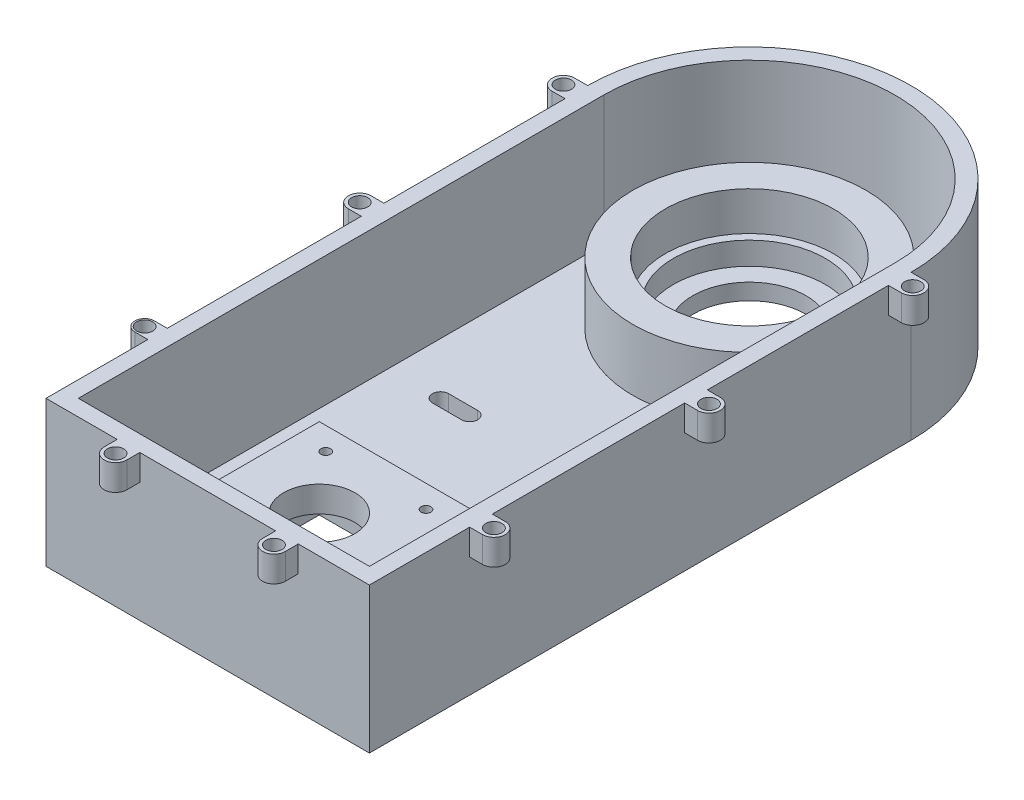
SolidWorks part; units mm, degrees
ref_plane "Front Plane" through (0, 0, 0) normal (0, 0, 1) x (1, 0, 0)
ref_plane "Top Plane" through (0, 0, 0) normal (0, 1, 0) x (1, 0, 0)
ref_plane "Right Plane" through (0, 0, 0) normal (1, 0, 0) x (0, 0, -1)
sketch "Sketch1" plane through (0, 0, 0) normal (0, 1, 0) x (1, 0, 0)
  line L0 (0, 0) -> (45, 0)
  line L1 (0, 0) -> (-45, 0)
  line L2 (0, 0) -> (0, -132.5)
  line L3 (0, -132.5) -> (0, -162.5)
  line L4 (-45, 0) -> (-45, -162.5)
  line L5 (0, -162.5) -> (45, -162.5)
  line L6 (45, 0) -> (45, -162.5)
  line L7 (0, -162.5) -> (-45, -162.5)
  line L8 (50, 0) -> (50, -167.5)
  line L9 (50, -167.5) -> (-50, -167.5)
  line L10 (-50, -167.5) -> (-50, 0)
  circle A0 centre (0, 0) radius 36
  arc A1 (-45, 0) -> (45, 0) centre (0, 0) cw
  arc A2 (-50, 0) -> (50, 0) centre (0, 0) cw
extrude "Boss-Extrude1" add sketch "Sketch1" along normal blind 5 contours L10 A2 L8 L9
sketch "Sketch2" plane through (0, 5, 0) normal (0, 1, 0) x (1, 0, 0)
  line L1 (-50, -167.5) -> (-50, 0) construction
  line L3 (-50, 0) -> (-45, 0)
  line L4 (-45, 0) -> (-45, -162.5)
  line L5 (-45, -162.5) -> (45, -162.5)
  line L6 (45, -162.5) -> (45, 0)
  arc A0 (-45, 0) -> (45, 0) centre (0, 0) cw
extrude "Boss-Extrude2" add sketch "Sketch2" along normal blind 40
sketch "Sketch3" plane through (0, 5, 0) normal (0, 1, 0) x (1, 0, 0)
  circle A0 centre (0, 0) radius 17.5
extrude "Cut-Extrude1" cut sketch "Sketch3" against normal blind 40
sketch "Sketch4" plane through (0, 5, 0) normal (0, 1, 0) x (1, 0, 0)
  circle A0 centre (0, 0) radius 23.5
  circle A1 centre (0, 0) radius 26
extrude "Boss-Extrude3" add sketch "Sketch4" along normal blind 7 contours A1 A0
sketch "Sketch5" plane through (0, 5, 0) normal (0, 1, 0) x (1, 0, 0)
  circle A0 centre (0, 0) radius 36
  circle M1 centre (0, 0) radius 26
extrude "Boss-Extrude4" add sketch "Sketch5" along normal blind 19 contours A0 M1
sketch "Sketch6" plane through (0, 5, 0) normal (0, 1, 0) x (1, 0, 0)
  line L2 (24.5, -133) -> (24.5, -157.5)
  line L3 (24.5, -157.5) -> (-24.5, -157.5)
  line L4 (-24.5, -157.5) -> (-24.5, -108.5)
  line L5 (-24.5, -108.5) -> (24.5, -108.5)
  line L6 (24.5, -108.5) -> (24.5, -133)
extrude "Boss-Extrude5" add sketch "Sketch6" along normal blind 17
sketch "Sketch7" plane through (0, 0, 0) normal (0, -1, 0) x (1, 0, 0)
  line L2 (21.5, 133) -> (21.5, 154.5)
  line L3 (21.5, 154.5) -> (-21.5, 154.5)
  line L4 (-21.5, 154.5) -> (-21.5, 111.5)
  line L5 (-21.5, 111.5) -> (21.5, 111.5)
  line L6 (21.5, 111.5) -> (21.5, 133)
extrude "Cut-Extrude2" cut sketch "Sketch7" against normal blind 14
sketch "Sketch8" plane through (0, 14, 0) normal (0, -1, 0) x (1, 0, 0)
  circle A1 centre (-15.5, 148.5) radius 1.5
  circle A2 centre (15.5, 148.5) radius 1.5
  circle A3 centre (-15.5, 115.5) radius 1.5
  circle A4 centre (15.5, 115.5) radius 1.5
  circle A5 centre (0, 133) radius 11
extrude "Cut-Extrude3" cut sketch "Sketch8" against normal blind 14
sketch "Sketch9" plane through (0, 45, 0) normal (0, 1, 0) x (1, 0, 0)
  line L0 (50, 0) -> (54, 0)
  line L1 (0, 0) -> (0, -133)
  line L2 (54, -7) -> (50, -7)
  line L5 (50, -167.5) -> (50, 0) construction
  line L10 (-20, -64) -> (-29, -64)
  line L11 (-20, -69) -> (-29, -69)
  line L12 (20, -64) -> (29, -64)
  line L13 (20, -69) -> (29, -69)
  arc A0 (54, 0) -> (54, -7) centre (54, -3.5) cw
  circle A1 centre (54, -3.5) radius 2.5
  circle A2 centre (0, -133) radius 2.5
  circle A5 centre (-20, -66.5) radius 2.5
  circle A6 centre (20, -66.5) radius 2.5
  arc A7 (-29, -64) -> (-29, -69) centre (-29, -66.5) ccw
  arc A9 (29, -64) -> (29, -69) centre (29, -66.5) cw
extrude "Cut-Extrude4" cut sketch "Sketch9" against normal blind 45 contours L10 A7 L11 A5 | A5 | A9 L12 A6 L13 | A6
sketch "Sketch10" plane through (0, 45, 0) normal (0, 1, 0) x (1, 0, 0)
  line L0 (50, 0) -> (54, 0)
  line L1 (20, -64) -> (20, -69)
  line L2 (54, -7) -> (50, -7)
  line L3 (50, -63) -> (54, -63)
  line L4 (50, -167.5) -> (50, 0) construction
  line L5 (50, -70) -> (54, -70)
  line L7 (50, -129.5) -> (54, -129.5)
  line L8 (50, -136.5) -> (54, -136.5)
  line L9 (-50, 0) -> (-54, 0)
  line L10 (-50, -7) -> (-54, -7)
  line L11 (-50, 0) -> (-50, -167.5) construction
  line L13 (-50, -63) -> (-54, -63)
  line L14 (-50, -70) -> (-54, -70)
  line L15 (-50, -130) -> (-54, -130)
  line L16 (-50, -136) -> (-54, -136)
  line L18 (21, -167.5) -> (21, -171.5)
  line L19 (-50, -167.5) -> (50, -167.5) construction
  line L20 (28, -167.5) -> (28, -171.5)
  line L21 (-21, -167.5) -> (-21, -171.5)
  line L22 (-28, -167.5) -> (-28, -171.5)
  arc A0 (54, 0) -> (54, -7) centre (54, -3.5) cw
  circle A1 centre (54, -3.5) radius 2.5
  arc A2 (20, -64) -> (20, -69) centre (20, -66.5) ccw construction
  circle A3 centre (54, -66.5) radius 2.5
  arc A4 (54, -63) -> (54, -70) centre (54, -66.5) cw
  circle A5 centre (54, -133) radius 2.5
  arc A6 (54, -129.5) -> (54, -136.5) centre (54, -133) cw
  circle A7 centre (-54, -3.5) radius 2.5
  arc A8 (-54, 0) -> (-54, -7) centre (-54, -3.5) ccw
  circle A9 centre (-54, -66.5) radius 2.5
  arc A10 (-54, -63) -> (-54, -70) centre (-54, -66.5) ccw
  circle A11 centre (-54, -133) radius 2.5
  arc A12 (-54, -130) -> (-54, -136) centre (-54, -133) ccw
  circle A13 centre (-24.5, -171.5) radius 2.5
  circle A14 centre (24.5, -171.5) radius 2.5
  arc A15 (-28, -171.5) -> (-21, -171.5) centre (-24.5, -171.5) ccw
  arc A16 (21, -171.5) -> (28, -171.5) centre (24.5, -171.5) ccw
  line M6 (-50, 0) -> (-50, -167.5)
  line M7 (-50, -167.5) -> (50, -167.5)
  line M8 (50, -167.5) -> (50, 0)
extrude "Boss-Extrude6" add sketch "Sketch10" against normal blind 8 contours L13 A10 L14 A9 M6 | L9 A8 L10 A7 M6 | L15 A12 L16 A11 M6 | L18 A16 L20 A14 M7 | L22 A15 L21 A13 M7 | A6 L7 L8 A5 M8 | A4 L3 L5 A3 M8 | A0 L0 L2 A1 M8
